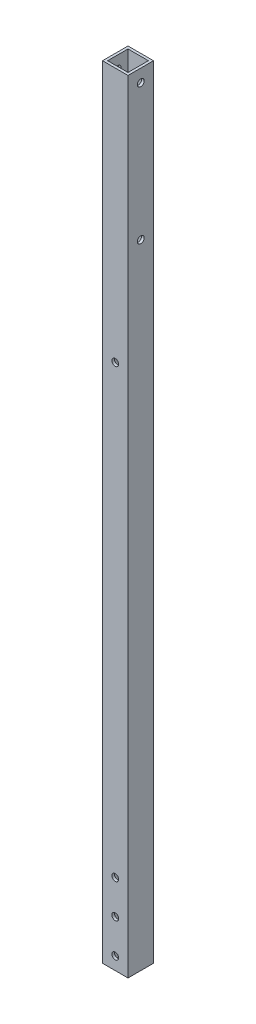
SolidWorks part; units mm, degrees
material "1060 合金"
ref_plane "正面" through (0, 0, 0) normal (0, 0, 1) x (1, 0, 0)
ref_plane "平面" through (0, 0, 0) normal (0, 1, 0) x (1, 0, 0)
ref_plane "右側面" through (0, 0, 0) normal (1, 0, 0) x (0, 0, -1)
sketch "ｽｹｯﾁ1" plane through (0, 0, 0) normal (0, 1, 0) x (1, 0, 0)
  line L1 (-7.5, -7.5) -> (7.5, -7.5)
  line L2 (-7.5, -7.5) -> (-7.5, 7.5)
  line L3 (-7.5, 7.5) -> (7.5, 7.5)
  line L4 (7.5, -7.5) -> (7.5, 7.5)
  line L5 (-7.5, -7.5) -> (7.5, 7.5) construction
  line L6 (-7.5, 7.5) -> (7.5, -7.5) construction
  point P0 (0, 0)
  dimension "D1" = 15
extrude "押し出し-薄板1" add sketch "ｽｹｯﾁ1" along normal blind 460 thin thin type one direction reverse wall 1.5
sketch "ｽｹｯﾁ2" plane through (7.5, 0, 0) normal (1, 0, 0) x (0, 0, -1)
  line L0 (0, 0) -> (0, 460) construction
  line L1 (-7.5, 460) -> (7.5, 460) construction
  circle A0 centre (0, 452.5) radius 2
  circle A1 centre (0, 372.5) radius 2
  dimension "D1" = 7.5
  dimension "D2" = 80
  dimension "D3" = 4
extrude "ｶｯﾄ - 押し出し1" cut sketch "ｽｹｯﾁ2" against normal through all
sketch "ｽｹｯﾁ3" plane through (0, 0, 7.5) normal (0, 0, 1) x (1, 0, 0)
  line L0 (0, 0) -> (0, 460) construction
  line L1 (-7.5, 460) -> (7.5, 460) construction
  line L2 (-7.5, 0) -> (7.5, 0) construction
  circle A0 centre (0, 7.5) radius 2
  circle A1 centre (0, 47.5) radius 2
  circle A2 centre (0, 27.5) radius 2
  circle A3 centre (0, 310) radius 2
  dimension "D1" = 7.5
  dimension "D2" = 40
  dimension "D3" = 4
  dimension "D4" = 20
  dimension "D5" = 150
  dimension "D6" = 4
extrude "ｶｯﾄ - 押し出し2" cut sketch "ｽｹｯﾁ3" against normal through all
